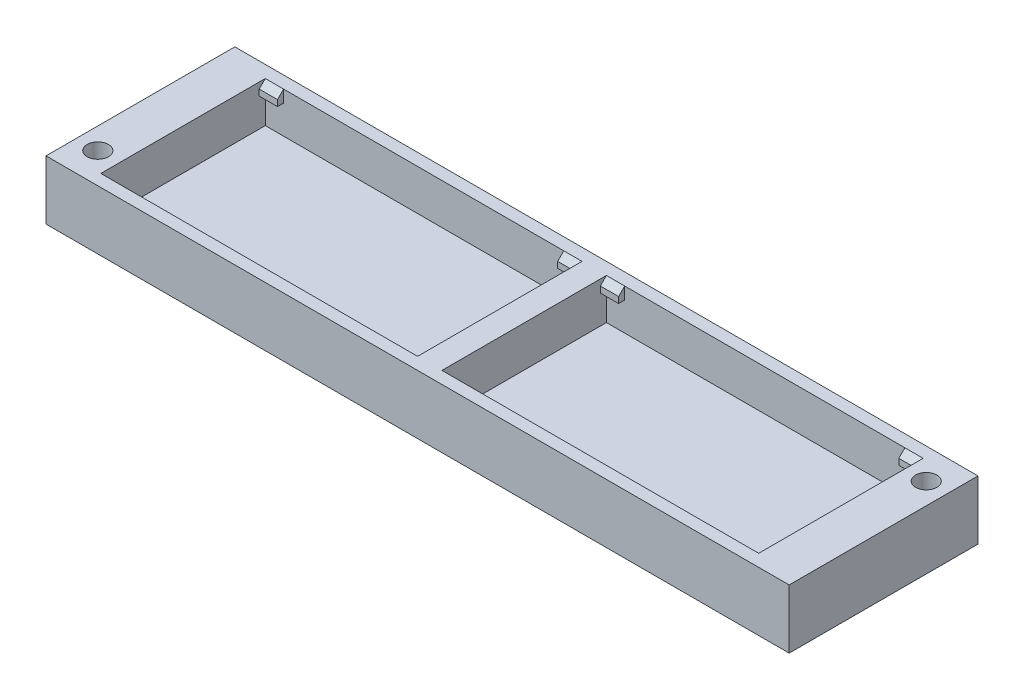
SolidWorks part; units mm, degrees
material "ABS"
ref_plane "Front Plane" through (0, 0, 0) normal (0, 0, 1) x (1, 0, 0)
ref_plane "Top Plane" through (0, 0, 0) normal (0, 1, 0) x (1, 0, 0)
ref_plane "Right Plane" through (0, 0, 0) normal (1, 0, 0) x (0, 0, -1)
sketch "Sketch1" plane through (0, 0, 0) normal (0, 1, 0) x (1, 0, 0)
  line L1 (-61, 15.5) -> (61, 15.5)
  line L2 (-61, 15.5) -> (-61, -15.5)
  line L3 (-61, -15.5) -> (61, -15.5)
  line L4 (61, 15.5) -> (61, -15.5)
  line L5 (-61, 15.5) -> (61, -15.5) construction
  line L6 (-61, -15.5) -> (61, 15.5) construction
  point P0 (0, 0)
  dimension "D1" = 122
  dimension "D2" = 31
extrude "Boss-Extrude1" add sketch "Sketch1" along normal blind 9.7
sketch "Sketch3" plane through (0, 9.7, 0) normal (0, 1, 0) x (1, 0, 0)
  line L0 (0, 15.5) -> (0, -15.5) construction
  line L1 (-54, 13.5) -> (-2, 13.5)
  line L2 (-54, 13.5) -> (-54, -13.5)
  line L3 (-54, -13.5) -> (-2, -13.5)
  line L4 (-2, 13.5) -> (-2, -13.5)
  line L5 (61, 15.5) -> (-61, 15.5) construction
  line L6 (-61, -15.5) -> (61, -15.5) construction
  line L7 (-61, 15.5) -> (-61, -15.5) construction
  line L8 (-61, 0) -> (61, 0) construction
  line L9 (61, -15.5) -> (61, 15.5) construction
  line L10 (54, -13.5) -> (2, -13.5)
  line L11 (2, 13.5) -> (2, -13.5)
  line L12 (54, 13.5) -> (2, 13.5)
  line L13 (54, 13.5) -> (54, -13.5)
  point P16 (-54, 0)
  dimension "D1" = 52
  dimension "D2" = 2
  dimension "D3" = 27
extrude "Cut-Extrude2" cut sketch "Sketch3" against normal offset from surface (6.7 mm away) 3 up to face at (0, 0, 0)
sketch "Sketch4" plane through (0, 9.7, 0) normal (0, 1, 0) x (1, 0, 0)
  line L0 (0, 15.5) -> (0, -15.5) construction
  line L1 (61, 15.5) -> (-61, 15.5) construction
  line L2 (-61, -15.5) -> (61, -15.5) construction
  line L3 (-54, 13.5) -> (-2, 13.5) construction
  line L4 (-54, 15.5) -> (-51, 15.5)
  line L5 (-54, 15.5) -> (-54, 12.5)
  line L6 (-54, 12.5) -> (-51, 12.5)
  line L7 (-51, 15.5) -> (-51, 12.5)
  line L8 (-5, 15.5) -> (-2, 15.5)
  line L9 (-5, 15.5) -> (-5, 12.5)
  line L10 (-5, 12.5) -> (-2, 12.5)
  line L11 (-2, 15.5) -> (-2, 12.5)
  line L12 (-2, -12.5) -> (-5, -12.5)
  line L13 (-2, -12.5) -> (-2, -15.5)
  line L14 (-2, -15.5) -> (-5, -15.5)
  line L15 (-5, -12.5) -> (-5, -15.5)
  line L16 (-54, -15.5) -> (-51, -15.5)
  line L17 (-54, -15.5) -> (-54, -12.5)
  line L18 (-54, -12.5) -> (-51, -12.5)
  line L19 (-51, -15.5) -> (-51, -12.5)
  line L38 (54, -12.5) -> (51, -12.5)
  line L39 (51, -15.5) -> (51, -12.5)
  line L40 (54, -15.5) -> (51, -15.5)
  line L41 (54, -15.5) -> (54, -12.5)
  line L42 (2, -15.5) -> (5, -15.5)
  line L43 (5, -12.5) -> (5, -15.5)
  line L44 (2, -12.5) -> (5, -12.5)
  line L45 (2, -12.5) -> (2, -15.5)
  line L46 (5, 12.5) -> (2, 12.5)
  line L47 (2, 15.5) -> (2, 12.5)
  line L48 (5, 15.5) -> (2, 15.5)
  line L49 (5, 15.5) -> (5, 12.5)
  line L50 (54, 12.5) -> (51, 12.5)
  line L51 (51, 15.5) -> (51, 12.5)
  line L52 (54, 15.5) -> (51, 15.5)
  line L53 (54, 15.5) -> (54, 12.5)
  line L54 (-2, -13.5) -> (-2, 13.5) construction
  line L55 (-54, 13.5) -> (-54, -13.5) construction
  dimension "D1" = 3
  dimension "D2" = 1
extrude "Boss-Extrude2" add sketch "Sketch4" against normal blind 2
chamfer "Chamfer1" distance 1 angle 45 8 edges at (-52.5, 9.7, 12.5) (-3.5, 9.7, 12.5) (52.5, 9.7, 12.5) (3.5, 9.7, 12.5) (52.5, 9.7, -12.5) (3.5, 9.7, -12.5) (-3.5, 9.7, -12.5) (-52.5, 9.7, -12.5)
sketch "Sketch5" plane through (0, 9.7, 0) normal (0, 1, 0) x (1, 0, 0)
  line L0 (-57.5, -15.5) -> (-57.5, 15.5) construction
  line L1 (-61, -15.5) -> (61, -15.5) construction
  line L2 (61, 15.5) -> (-61, 15.5) construction
  line L3 (0, 15.5) -> (0, -15.5) construction
  line L4 (-61, 15.5) -> (-61, -15.5) construction
  line L5 (57.5, -15.5) -> (57.5, 15.5) construction
  line L6 (-61, 0) -> (61, 0) construction
  line L7 (61, -15.5) -> (61, 15.5) construction
  circle A0 centre (-57.5, -10.5) radius 1.75
  circle A1 centre (57.5, 10.5) radius 1.75
  dimension "D2" = 3.5
  dimension "D5" = 3.5
  dimension "D1" = 3.5
  dimension "D3" = 5
  dimension "D4" = 5
extrude "Cut-Extrude3" cut sketch "Sketch5" against normal through all
